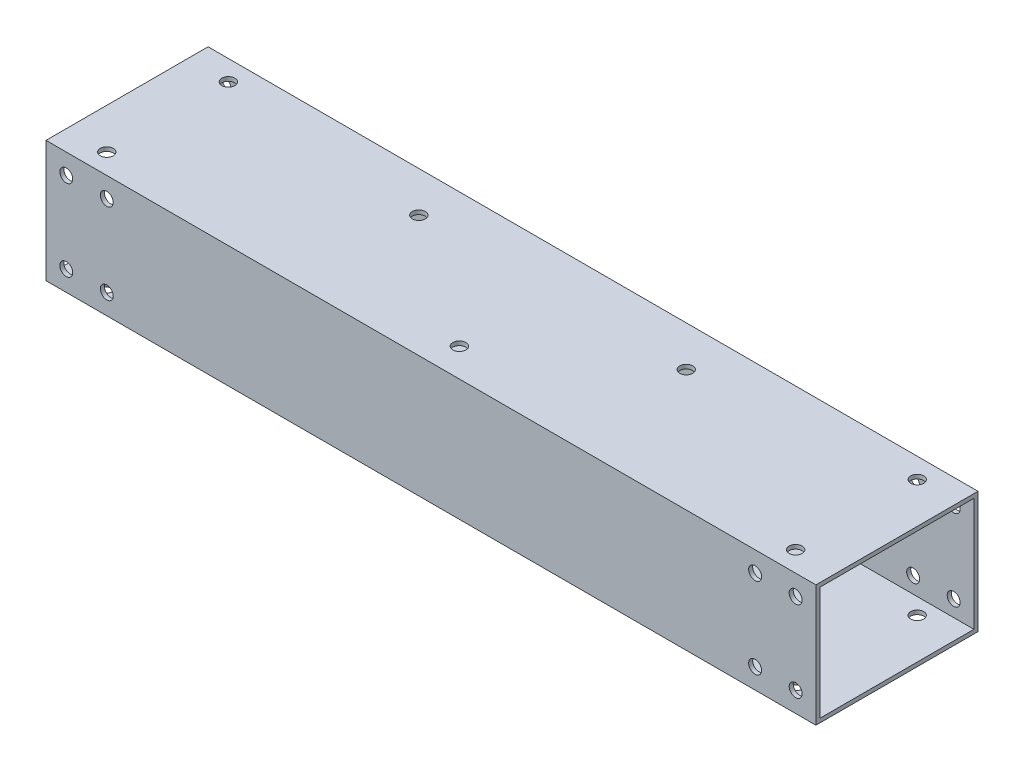
SolidWorks part; units mm, degrees
material "6061 合金"
ref_plane "前视基准面" through (0, 0, 0) normal (0, 0, 1) x (1, 0, 0)
ref_plane "上视基准面" through (0, 0, 0) normal (0, 1, 0) x (1, 0, 0)
ref_plane "右视基准面" through (0, 0, 0) normal (1, 0, 0) x (0, 0, -1)
sketch "草图1" plane through (0, 0, 0) normal (1, 0, 0) x (0, 0, -1)
  line L0 (-19, 14) -> (-19, -14)
  line L1 (-20, 15) -> (20, 15)
  line L2 (-20, 15) -> (-20, -15)
  line L3 (-20, -15) -> (20, -15)
  line L4 (20, 15) -> (20, -15)
  line L5 (-20, 15) -> (20, -15) construction
  line L6 (-20, -15) -> (20, 15) construction
  line L7 (-19, -14) -> (19, -14)
  line L8 (19, 14) -> (19, -14)
  line L9 (-19, 14) -> (19, 14)
  point P0 (0, 0)
  dimension "D1" = 1
  dimension "D2" = 40
  dimension "D3" = 30
extrude "凸台-拉伸1" add sketch "草图1" along normal mid plane 190
sketch "草图2" plane through (0, 15, 0) normal (0, 1, 0) x (1, 0, 0)
  line L0 (0, 82.3869) -> (0, -87.0517) construction
  line L1 (-165.1588, 0) -> (152.4609, 0) construction
  line L2 (95, -20) -> (-95, -20) construction
  line L3 (-95, 20) -> (-95, -20) construction
  circle A0 centre (0, -13) radius 1.6
  circle A1 centre (-33, 10) radius 1.6
  circle A2 centre (33, 10) radius 1.6
  circle A3 centre (-85, 15) radius 1.6
  circle A4 centre (-85, -15) radius 1.6
  circle A5 centre (85, -15) radius 1.6
  circle A6 centre (85, 15) radius 1.6
  dimension "D1" = 3.2
  dimension "D2" = 7
  dimension "D3" = 30
  dimension "D4" = 66
  dimension "D5" = 5
  dimension "D6" = 10
extrude "切除-拉伸1" cut sketch "草图2" against normal through all both and the other way through all
sketch "草图3" plane through (0, 0, 20) normal (0, 0, 1) x (1, 0, 0)
  line L0 (0, 34.4049) -> (0, -45.9549) construction
  line L1 (-105.937, 0) -> (105.374, 0) construction
  line L2 (-95, 15) -> (-95, -15) construction
  circle A0 centre (-90, 10) radius 1.6
  circle A1 centre (-90, -10) radius 1.6
  circle A2 centre (-80, 10) radius 1.6
  circle A3 centre (-80, -10) radius 1.6
  circle A4 centre (80, -10) radius 1.6
  circle A5 centre (80, 10) radius 1.6
  circle A6 centre (90, -10) radius 1.6
  circle A7 centre (90, 10) radius 1.6
  point P9 (0, 0)
  dimension "D1" = 3.2
  dimension "D2" = 5
  dimension "D3" = 10
  dimension "D4" = 20
extrude "切除-拉伸2" cut sketch "草图3" against normal through all
